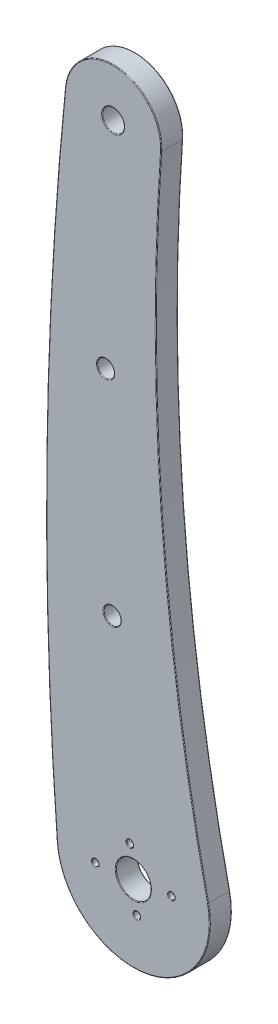
SolidWorks part; units mm, degrees
ref_plane "Front Plane" through (0, 0, 0) normal (0, 0, 1) x (1, 0, 0)
ref_plane "Top Plane" through (0, 0, 0) normal (0, 1, 0) x (1, 0, 0)
ref_plane "Right Plane" through (0, 0, 0) normal (1, 0, 0) x (0, 0, -1)
sketch "Sketch1" plane through (0, 0, 0) normal (0, 0, 1) x (1, 0, 0)
  line L0 (-20.22, 57.58) -> (-24.8517, 205.5075) construction
  line L1 (-20.22, 57.58) -> (-24.8517, 205.5075) construction
  circle A0 centre (-24.8517, 205.5075) radius 11 construction
  circle A1 centre (-20.22, 57.58) radius 17.5 construction
  circle A2 centre (-24.8517, 205.5075) radius 11 construction
  circle A3 centre (-20.22, 57.58) radius 17.5 construction
  circle A4 centre (-24.8517, 205.5075) radius 2.5
  circle A7 centre (-20.22, 57.58) radius 4
  arc A8 (-13.8783, 204.7438) -> (-3.1381, 61.3826) centre (484.9152, 170.0288) ccw
  arc A9 (-35.7956, 206.617) -> (-37.6693, 56.2493) centre (809.8697, 120.8837) ccw
  arc A10 (-24.8517, 205.5075) -> (-20.22, 57.58) centre (723.439, 154.9008) ccw construction
  arc A11 (-35.7956, 206.617) -> (-13.8783, 204.7438) centre (-24.8517, 205.5075) cw
  arc A12 (-37.6693, 56.2493) -> (-3.1381, 61.3826) centre (-20.22, 57.58) ccw
  circle A13 centre (-21.0272, 64.2816) radius 0.75
  circle A14 centre (-28.9072, 56.5336) radius 0.75
  circle A15 centre (-11.5328, 58.6264) radius 0.75
  circle A16 centre (-19.4128, 50.8784) radius 0.75
  point P17 (-26.5608, 155.5367)
  point P18 (-25.0519, 107.346)
  dimension "D1" = 8
  dimension "D2" = 5
  dimension "D3" = 500
  dimension "D4" = 850
  dimension "D5" = 750
  dimension "D6" = 50
  dimension "D7" = 50
extrude "Boss-Extrude4" add sketch "Sketch1" against normal blind 5
hole_wizard "M3.5 Clearance Hole1" positions "Sketch2" profile "Sketch3" hole size "M3.5" standard "ISO" end condition up to next
sketch "Sketch2" plane through (0, 0, 0) normal (0, 0, 1) x (1, 0, 0)
  point P0 (-25.0519, 107.346)
  point P3 (-26.5608, 155.5367)
sketch "Sketch3" plane through (-25.0519, 107.346, 0) normal (1, 0, 0) x (0, -1, 0)
  line L0 (0, 0) -> (0, 5)
  line L1 (0, 5) -> (1.95, 5)
  line L2 (1.95, 5) -> (1.95, 0)
  line L5 (1.95, 0) -> (0, 0)
  line L11 (0, -6.35) -> (0, 107.95) construction
  dimension "Thru Hole Dia." = 3.9
  dimension "Thru Hole Depth" = 5
fillet "Fillet1" radius 0.15 24 edges at (-40.0643, 131.4747, -5) (-17.6468, 40.2702, -5) (-13.6876, 132.6752, -5) (-23.915, 216.4675, -5) (-22.3517, 205.5075, -5) (-16.22, 57.58, -5) (-28.5108, 155.5367, -5) (-27.0019, 107.346, -5) (-23.1019, 107.346, 0) (-24.6108, 155.5367, 0) (-13.6876, 132.6752, 0) (-17.6468, 40.2702, 0) (-40.0643, 131.4747, 0) (-23.915, 216.4675, 0) (-22.3517, 205.5075, 0) (-16.22, 57.58, 0) (-20.2772, 64.2816, -5) (-28.1572, 56.5336, -5) (-10.7828, 58.6264, -5) (-18.6628, 50.8784, -5) (-20.2772, 64.2816, 0) (-28.1572, 56.5336, 0) (-10.7828, 58.6264, 0) (-18.6628, 50.8784, 0)
